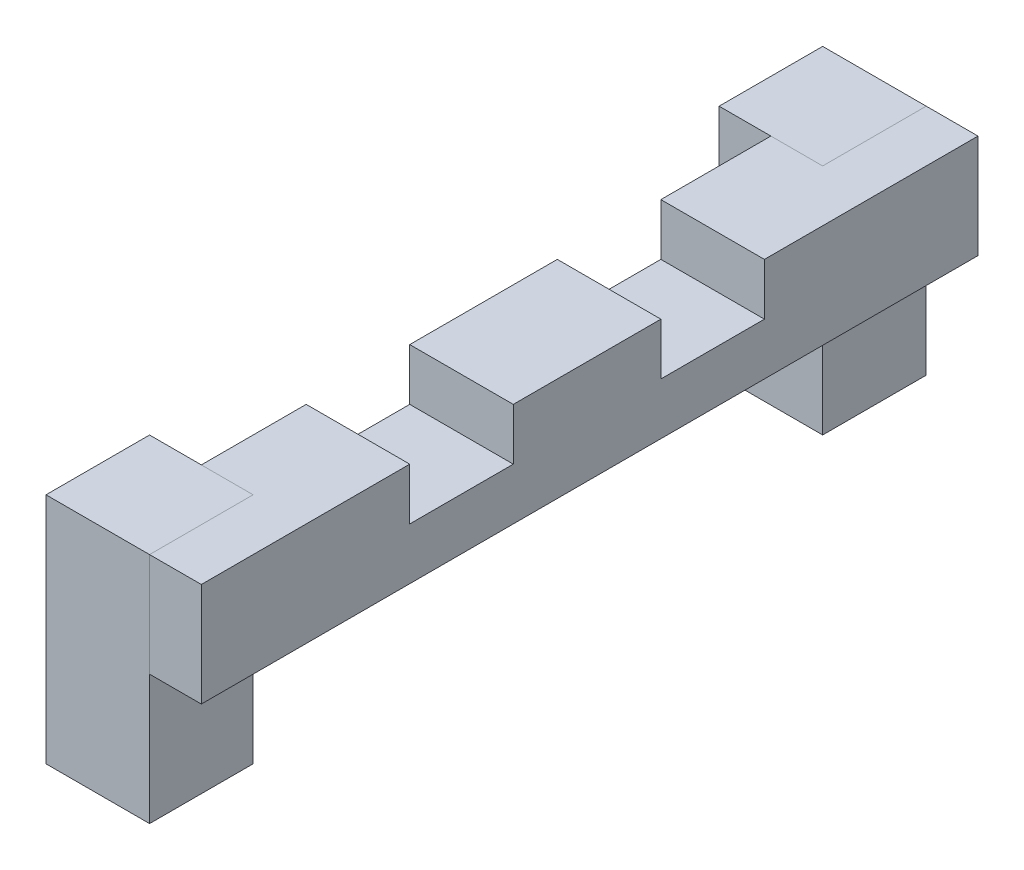
SolidWorks part; units mm, degrees
ref_plane "Front Plane" through (0, 0, 0) normal (0, 0, 1) x (1, 0, 0)
ref_plane "Top Plane" through (0, 0, 0) normal (0, 1, 0) x (1, 0, 0)
ref_plane "Right Plane" through (0, 0, 0) normal (1, 0, 0) x (0, 0, -1)
sketch "Sketch1" plane through (0, 0, 0) normal (0, 1, 0) x (1, 0, 0)
  line L1 (0, 0) -> (40, 0)
  line L2 (0, 0) -> (0, -300)
  line L3 (0, -300) -> (40, -300)
  line L4 (40, 0) -> (40, -300)
  dimension "D1" = 40
  dimension "D2" = 300
extrude "Boss-Extrude1" add sketch "Sketch1" along normal blind 40
sketch "Sketch2" plane through (0, 40, 0) normal (0, 1, 0) x (1, 0, 0)
  line L0 (0, 0) -> (0, -300) construction
  line L1 (0, -82.5) -> (40, -82.5)
  line L2 (0, -82.5) -> (0, -122.5)
  line L3 (0, -122.5) -> (40, -122.5)
  line L4 (40, -82.5) -> (40, -122.5)
  line L5 (40, -300) -> (40, 0) construction
  line L6 (40, 0) -> (0, 0) construction
  line L7 (0, -179.5) -> (40, -179.5)
  line L8 (0, -179.5) -> (0, -219.5)
  line L9 (0, -219.5) -> (40, -219.5)
  line L10 (40, -179.5) -> (40, -219.5)
  dimension "D1" = 40
  dimension "D2" = 40
  dimension "D3" = 57
  dimension "85" = 82.5
extrude "Cut-Extrude1" cut sketch "Sketch2" against normal blind 20
sketch "Sketch7" plane through (0, 0, 300) normal (0, 0, 1) x (1, 0, 0)
  line L0 (20, 40) -> (20, 0)
  line L4 (0, 0) -> (40, 0)
  line L5 (40, 0) -> (40, 40)
  line L6 (40, 40) -> (0, 40)
  line L7 (0, 40) -> (0, 0)
  line L8 (0, 0) -> (20, 0)
  line L10 (20, 40) -> (0, 40)
  line L11 (0, 40) -> (0, 0)
  dimension "D1" = 0
extrude "Cut-Extrude4" cut sketch "Sketch7" against normal blind 40
sketch "Sketch3" plane through (0, 0, 300) normal (0, 0, 1) x (1, 0, 0)
  line L2 (-366.9864, -50) -> (-137.7521, -50) construction
  line L3 (20, 0) -> (40, 0) construction
  line L6 (-38.7954, -50) -> (450.9307, -50) construction
  line L8 (20, 40) -> (20, -50)
  line L16 (20, -50) -> (-20, -50)
  line L17 (-20, -50) -> (-20, 40)
  line L18 (-20, 40) -> (20, 40)
  dimension "D1" = 50
  dimension "D2" = 40
extrude "Boss-Extrude2" add sketch "Sketch3" against normal blind 40 separate body
ref_plane "Plane1" through (0, 0, 150) normal (0, 0, -1) x (-1, 0, 0)
sketch "Sketch6" plane through (0, 0, 0) normal (0, 0, -1) x (-1, 0, 0)
  line L0 (-20, 40) -> (-20, 0)
  line L4 (-40, 0) -> (0, 0)
  line L5 (0, 0) -> (0, 40)
  line L6 (0, 40) -> (-40, 40)
  line L7 (-40, 40) -> (-40, 0)
  line L8 (-20, 0) -> (0, 0)
  line L9 (0, 0) -> (0, 40)
  line L10 (0, 40) -> (-20, 40)
  dimension "D1" = 0
extrude "Cut-Extrude3" cut sketch "Sketch6" against normal blind 40
sketch "Sketch4" plane through (0, 0, 0) normal (0, 0, -1) x (-1, 0, 0)
  line L18 (20, 40) -> (-20, 40)
  line L19 (-20, 40) -> (-20, -50)
  line L20 (-20, -50) -> (20, -50)
  line L21 (20, -50) -> (20, 40)
  line L22 (20, 40) -> (-20, 40)
  line L23 (-20, 40) -> (-20, -50)
  line L24 (-20, -50) -> (20, -50)
  line L25 (20, -50) -> (20, 40)
  dimension "D1" = 0
extrude "Boss-Extrude3" add sketch "Sketch4" against normal blind 40 separate body
